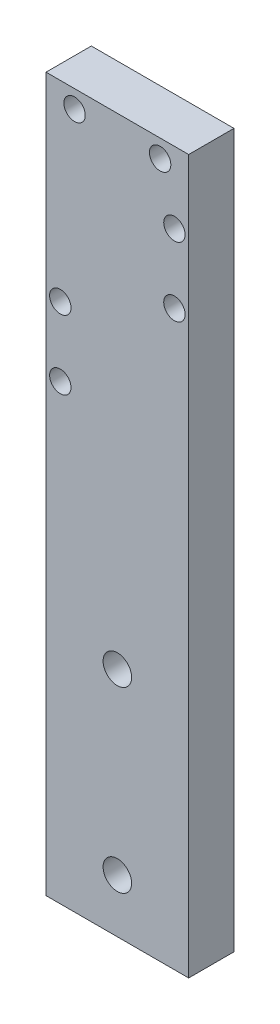
SolidWorks part; units mm, degrees
ref_plane "Front Plane" through (0, 0, 0) normal (0, 0, 1) x (1, 0, 0)
ref_plane "Top Plane" through (0, 0, 0) normal (0, 1, 0) x (1, 0, 0)
ref_plane "Right Plane" through (0, 0, 0) normal (1, 0, 0) x (0, 0, -1)
sketch "Sketch1" plane through (0, 0, 0) normal (0, 0, 1) x (1, 0, 0)
  line L1 (0, 0) -> (20, 0)
  line L2 (0, 0) -> (0, 40)
  line L3 (0, 40) -> (20, 40)
  line L4 (20, 0) -> (20, 40)
  circle A0 centre (10, 32.5) radius 2
  circle A1 centre (10, 7.5) radius 2
  point P9 (0, 0)
  dimension "D5" = 4
  dimension "D1" = 20
  dimension "D2" = 40
  dimension "D3" = 10
  dimension "D4" = 7.5
  dimension "D6" = 25
extrude "Boss-Extrude1" add sketch "Sketch1" along normal blind 6.35
sketch "Sketch3" plane through (0, 40, 0) normal (0, 1, 0) x (1, 0, 0)
  line L1 (20, -6.35) -> (0, -6.35)
  line L2 (20, -6.35) -> (20, 0)
  line L3 (20, 0) -> (0, 0)
  line L4 (0, -6.35) -> (0, 0)
extrude "Boss-Extrude3" add sketch "Sketch3" along normal blind 60
sketch "Sketch6" plane through (0, 0, 0) normal (0, 0, -1) x (-1, 0, 0)
  line L0 (-20, 0) -> (-20, 100) construction
  line L1 (-20, 100) -> (0, 100) construction
  line L2 (-20, 0) -> (-20, 100) construction
  line L3 (0, 100) -> (0, 0) construction
  circle A0 centre (-16, 97.5) radius 1.5
  circle A1 centre (-4, 97.5) radius 1.5
  circle A2 centre (-18, 90) radius 1.5
  circle A3 centre (-2, 63.4482) radius 1.5
  circle A5 centre (-2, 73.131) radius 1.5
  circle A6 centre (-18, 80.3171) radius 1.5
  point P16 (0, 0)
  point P25 (-2, 88.6831)
  dimension "D1" = 3
  dimension "D2" = 3
  dimension "D4" = 4
  dimension "D7" = 3
  dimension "D8" = 10
  dimension "D3" = 12
  dimension "D5" = 2.5
  dimension "D6" = 2
  dimension "D9" = 2
  dimension "D10" = 31
  dimension "D11" = 23.25
  dimension "D12" = 23.25
extrude "Cut-Extrude1" cut sketch "Sketch6" against normal blind 23.2
